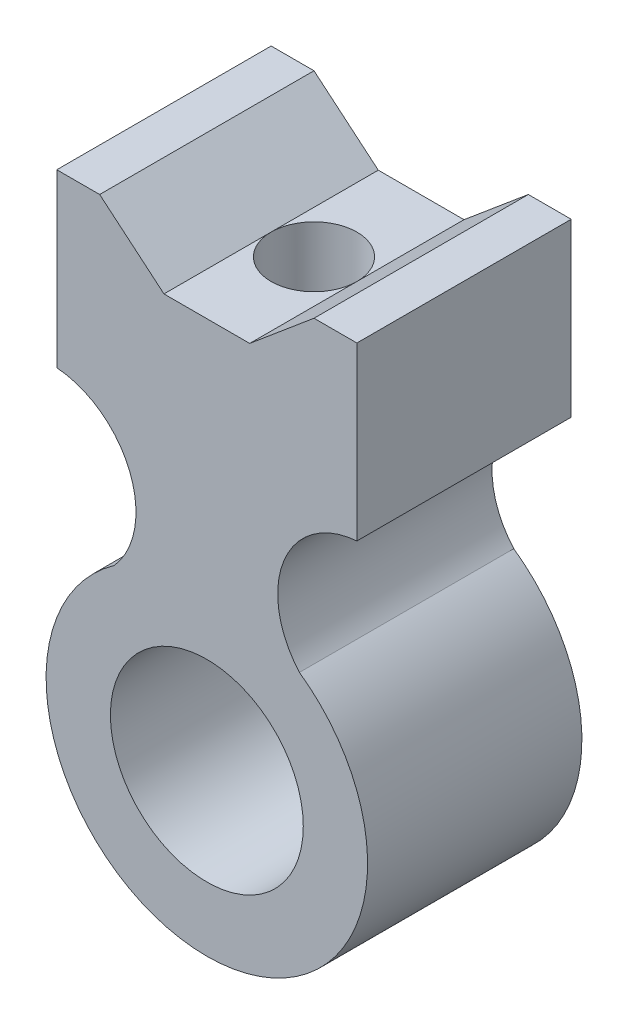
SolidWorks part; units mm, degrees
ref_plane "Front Plane" through (0, 0, 0) normal (0, 0, 1) x (1, 0, 0)
ref_plane "Top Plane" through (0, 0, 0) normal (0, 1, 0) x (1, 0, 0)
ref_plane "Right Plane" through (0, 0, 0) normal (1, 0, 0) x (0, 0, -1)
sketch "Sketch1" plane through (0, 0, 0) normal (0, 0, 1) x (1, 0, 0)
  line L0 (0, 22.5) -> (0, 119.6233) construction
  line L3 (0, 22.5) -> (0, -83.6219) construction
  line L4 (-25, 103.9034) -> (-10, 91.3169)
  line L5 (-10, 91.3169) -> (10, 91.3169)
  line L6 (-25, 103.9034) -> (-35, 103.9034)
  line L7 (-35, 103.9034) -> (-35, 63.9034)
  line L8 (-65.6985, 91.3169) -> (57.4533, 91.3169) construction
  line L9 (-40.81, 30.6496) -> (38.2243, 30.6496) construction
  line L10 (35, 103.9034) -> (35, 63.9034)
  line L11 (25, 103.9034) -> (35, 103.9034)
  line L12 (25, 103.9034) -> (10, 91.3169)
  circle A0 centre (0, 0) radius 22.5
  arc A1 (-21.6067, 30.6496) -> (21.6067, 30.6496) centre (0, 0) ccw
  arc A2 (-35, 63.9034) -> (-21.6067, 30.6496) centre (-36.5324, 43.9621) cw
  arc A3 (35, 63.9034) -> (21.6067, 30.6496) centre (36.5324, 43.9621) ccw
  point P15 (0, 113.5956)
  point P18 (0, 0)
  point P22 (-43.8351, 63.9034)
  point P25 (0, 91.3169)
  dimension "D1" = 20
  dimension "D4" = 45
  dimension "D5" = 37.5
  dimension "D9" = 33.2537
  dimension "D2" = 40
  dimension "D3" = 10
  dimension "D6" = 35
  dimension "D7" = 10
  dimension "D8" = 40
extrude "Boss-Extrude1" add sketch "Sketch1" along normal blind 50
sketch "Sketch3" plane through (0, 91.3169, 0) normal (0, 1, 0) x (1, 0, 0)
  circle A0 centre (0, -25) radius 10
  dimension "D2" = 20
  dimension "D1" = 25
extrude "Cut-Extrude1" cut sketch "Sketch3" against normal up to next
